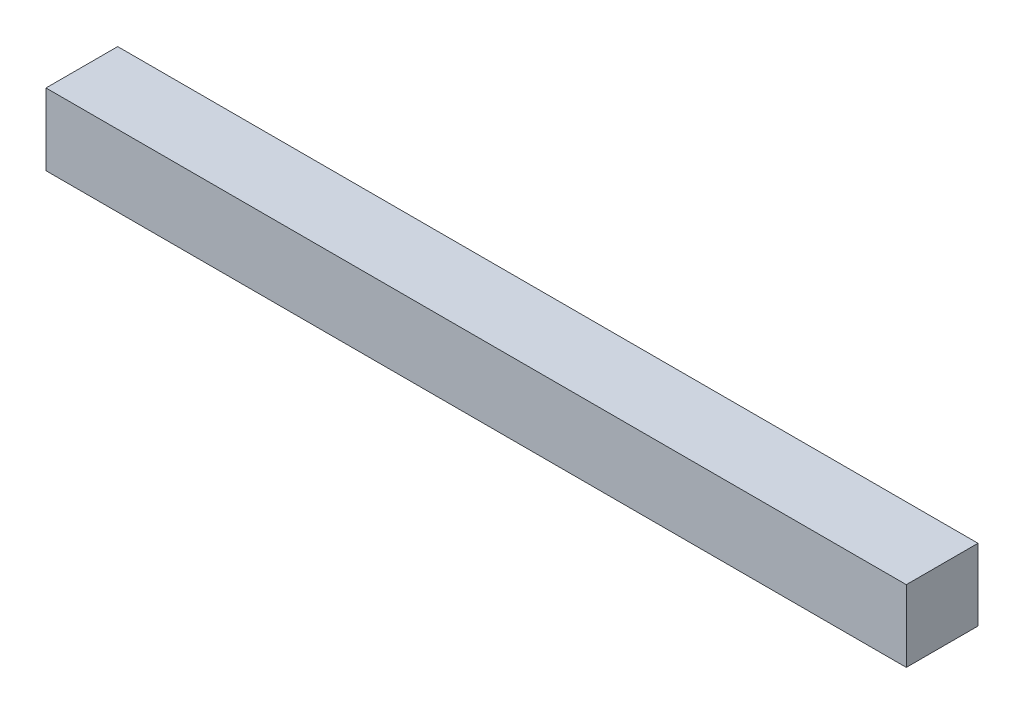
SolidWorks part; units mm, degrees
ref_plane "Front Plane" through (0, 0, 0) normal (0, 0, 1) x (1, 0, 0)
ref_plane "Top Plane" through (0, 0, 0) normal (0, 1, 0) x (1, 0, 0)
ref_plane "Right Plane" through (0, 0, 0) normal (1, 0, 0) x (0, 0, -1)
sketch "Sketch1" plane through (0, 0, 0) normal (1, 0, 0) x (0, 0, -1)
  line L1 (0, 0) -> (-25.4, 0)
  line L2 (0, 0) -> (0, -25.4)
  line L3 (0, -25.4) -> (-25.4, -25.4)
  line L4 (-25.4, 0) -> (-25.4, -25.4)
  dimension "D1" = 25.4
  dimension "D2" = 25.4
extrude "Boss-Extrude1" add sketch "Sketch1" along normal blind 304.8 contours L1 L4 L3 L2
